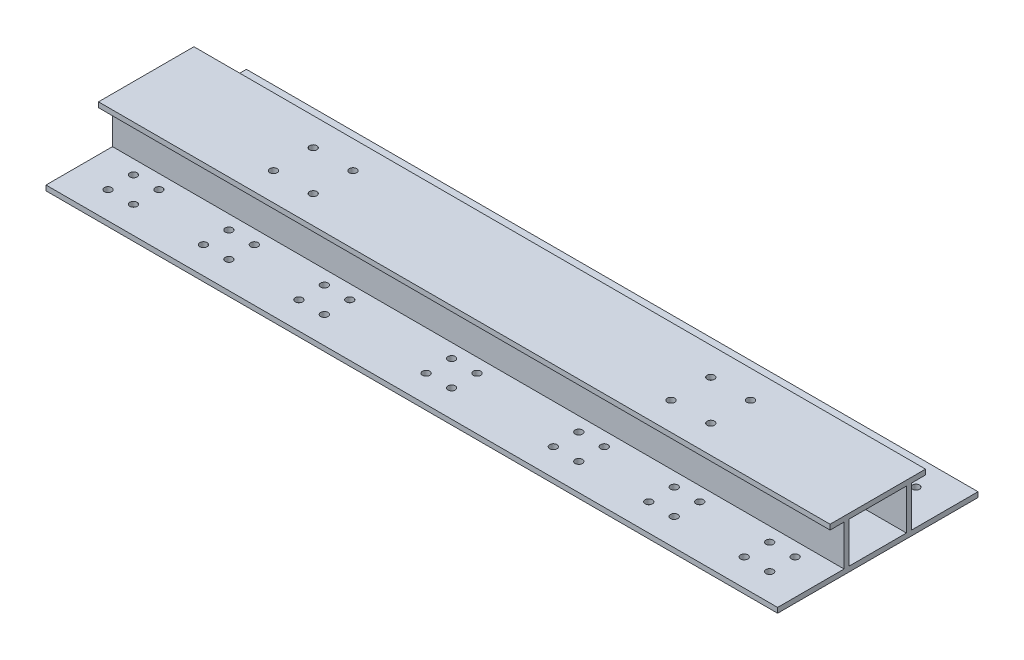
SolidWorks part; units mm, degrees
ref_plane "前视基准面" through (0, 0, 0) normal (0, 0, 1) x (1, 0, 0)
ref_plane "上视基准面" through (0, 0, 0) normal (0, 1, 0) x (1, 0, 0)
ref_plane "右视基准面" through (0, 0, 0) normal (1, 0, 0) x (0, 0, -1)
sketch "草图7" plane through (0, 0, 0) normal (1, 0, 0) x (0, 0, -1)
  line L0 (0, -1000) -> (0, 49000) construction
  line L1 (-1000, 0) -> (49000, 0) construction
  line L2 (-315, 16) -> (-315, 0)
  line L3 (-315, 0) -> (315, 0)
  line L4 (315, 0) -> (315, 16)
  line L5 (315, 16) -> (106, 16)
  line L6 (-106, 144) -> (-106, 16)
  line L7 (106, 144) -> (150, 144)
  line L8 (150, 144) -> (150, 160)
  line L9 (150, 160) -> (-150, 160)
  line L10 (-150, 160) -> (-150, 144)
  line L11 (-150, 144) -> (-106, 144)
  line L12 (106, 144) -> (106, 16)
  line L13 (-106, 16) -> (-315, 16)
  line L14 (-90, 144) -> (-90, 16)
  line L15 (-90, 16) -> (90, 16)
  line L16 (90, 16) -> (90, 144)
  line L17 (90, 144) -> (-90, 144)
  dimension "D1" = 630
  dimension "D2" = 16
  dimension "D3" = 16
  dimension "D4" = 16
  dimension "D5" = 16
  dimension "D6" = 160
  dimension "D7" = 300
  dimension "D8" = 180
extrude "凸台-拉伸1" add sketch "草图7" along normal blind 2300
sketch "草图8" plane through (0, 160, 0) normal (0, 1, 0) x (1, 0, 0)
  line L0 (1300, 0) -> (51300, 0) construction
  line L1 (2300, 150) -> (2300, -150) construction
  line L3 (1150, -850) -> (1150, 49150) construction
  line L4 (2300, 150) -> (0, 150) construction
  circle A0 centre (462.5, 62.5) radius 11.5
  circle A1 centre (587.5, 62.5) radius 11.5
  circle A2 centre (462.5, -62.5) radius 11.5
  circle A3 centre (587.5, -62.5) radius 11.5
  circle A4 centre (1712.5, 62.5) radius 11.5
  circle A5 centre (1837.5, 62.5) radius 11.5
  circle A6 centre (1712.5, -62.5) radius 11.5
  circle A7 centre (1837.5, -62.5) radius 11.5
  point P6 (2300, 0)
  point P12 (1150, 150)
  dimension "D1" = 23
  dimension "D2" = 125
  dimension "D3" = 125
  dimension "D4" = 1125
extrude "切除-拉伸1" cut sketch "草图8" against normal blind 16
sketch "草图9" plane through (0, 0, 0) normal (0, -1, 0) x (1, 0, 0)
  line L0 (1300, 0) -> (51300, 0) construction
  line L1 (2300, 315) -> (2300, -315) construction
  line L2 (110, -751.0037) -> (110, 49248.9963) construction
  line L4 (-1000, 150) -> (49000, 150) construction
  line L6 (-950.393, -150) -> (49049.607, -150) construction
  line L7 (-1000, 230) -> (49000, 230) construction
  line L9 (-884.8038, -230) -> (49115.1962, -230) construction
  line L10 (190, -792.3006) -> (190, 49207.6994) construction
  line L11 (410, -787.4422) -> (410, 49212.5578) construction
  line L12 (490, -785.0129) -> (490, 49214.9871) construction
  line L13 (710, -780.1545) -> (710, 49219.8455) construction
  line L14 (790, -792.3006) -> (790, 49207.6994) construction
  line L15 (1110, -782.5837) -> (1110, 49217.4163) construction
  line L16 (1190, -763.1499) -> (1190, 49236.8501) construction
  line L17 (1510, -775.296) -> (1510, 49224.704) construction
  line L18 (1590, -772.8668) -> (1590, 49227.1332) construction
  line L19 (1810, -775.296) -> (1810, 49224.704) construction
  line L20 (1890, -782.5837) -> (1890, 49217.4163) construction
  line L21 (2110, -785.0129) -> (2110, 49214.9871) construction
  line L22 (2190, -785.0129) -> (2190, 49214.9871) construction
  line L24 (0, 315) -> (0, -315) construction
  circle A0 centre (110, 230) radius 11.5
  circle A1 centre (190, 230) radius 11.5
  circle A2 centre (410, 230) radius 11.5
  circle A3 centre (490, 230) radius 11.5
  circle A4 centre (710, 230) radius 11.5
  circle A5 centre (790, 230) radius 11.5
  circle A6 centre (110, 150) radius 11.5
  circle A7 centre (190, 150) radius 11.5
  circle A8 centre (410, 150) radius 11.5
  circle A9 centre (490, 150) radius 11.5
  circle A10 centre (710, 150) radius 11.5
  circle A11 centre (790, 150) radius 11.5
  circle A12 centre (110, -150) radius 11.5
  circle A13 centre (190, -150) radius 11.5
  circle A14 centre (190, -230) radius 11.5
  circle A15 centre (110, -230) radius 11.5
  circle A16 centre (410, -150) radius 11.5
  circle A17 centre (490, -150) radius 11.5
  circle A18 centre (410, -230) radius 11.5
  circle A19 centre (490, -230) radius 11.5
  circle A20 centre (710, -150) radius 11.5
  circle A21 centre (790, -150) radius 11.5
  circle A22 centre (710, -230) radius 11.5
  circle A23 centre (790, -230) radius 11.5
  circle A24 centre (1110, -150) radius 11.5
  circle A25 centre (1110, -230) radius 11.5
  circle A26 centre (1190, -150) radius 11.5
  circle A27 centre (1190, -230) radius 11.5
  circle A28 centre (1110, 230) radius 11.5
  circle A29 centre (1110, 150) radius 11.5
  circle A30 centre (1190, 230) radius 11.5
  circle A31 centre (1190, 150) radius 11.5
  circle A32 centre (1510, 230) radius 11.5
  circle A33 centre (1510, 150) radius 11.5
  circle A34 centre (1590, 230) radius 11.5
  circle A35 centre (1590, 150) radius 11.5
  circle A36 centre (1510, -150) radius 11.5
  circle A37 centre (1590, -150) radius 11.5
  circle A38 centre (1510, -230) radius 11.5
  circle A39 centre (1590, -230) radius 11.5
  circle A40 centre (1810, 230) radius 11.5
  circle A41 centre (1890, 230) radius 11.5
  circle A42 centre (1810, 150) radius 11.5
  circle A43 centre (1890, 150) radius 11.5
  circle A44 centre (1810, -150) radius 11.5
  circle A45 centre (1890, -150) radius 11.5
  circle A46 centre (1810, -230) radius 11.5
  circle A47 centre (1890, -230) radius 11.5
  circle A48 centre (2110, 230) radius 11.5
  circle A49 centre (2190, 230) radius 11.5
  circle A50 centre (2110, 150) radius 11.5
  circle A51 centre (2190, 150) radius 11.5
  circle A52 centre (2110, -150) radius 11.5
  circle A53 centre (2190, -150) radius 11.5
  circle A54 centre (2110, -230) radius 11.5
  circle A55 centre (2190, -230) radius 11.5
  point P5 (2300, 0)
  dimension "D19" = 23
  dimension "D1" = 150
  dimension "D2" = 150
  dimension "D3" = 80
  dimension "D4" = 80
  dimension "D5" = 110
  dimension "D6" = 80
  dimension "D7" = 220
  dimension "D8" = 80
  dimension "D9" = 220
  dimension "D10" = 80
  dimension "D11" = 320
  dimension "D12" = 80
  dimension "D13" = 320
  dimension "D14" = 80
  dimension "D15" = 220
  dimension "D16" = 80
  dimension "D17" = 220
  dimension "D18" = 80
extrude "切除-拉伸2" cut sketch "草图9" against normal blind 16
